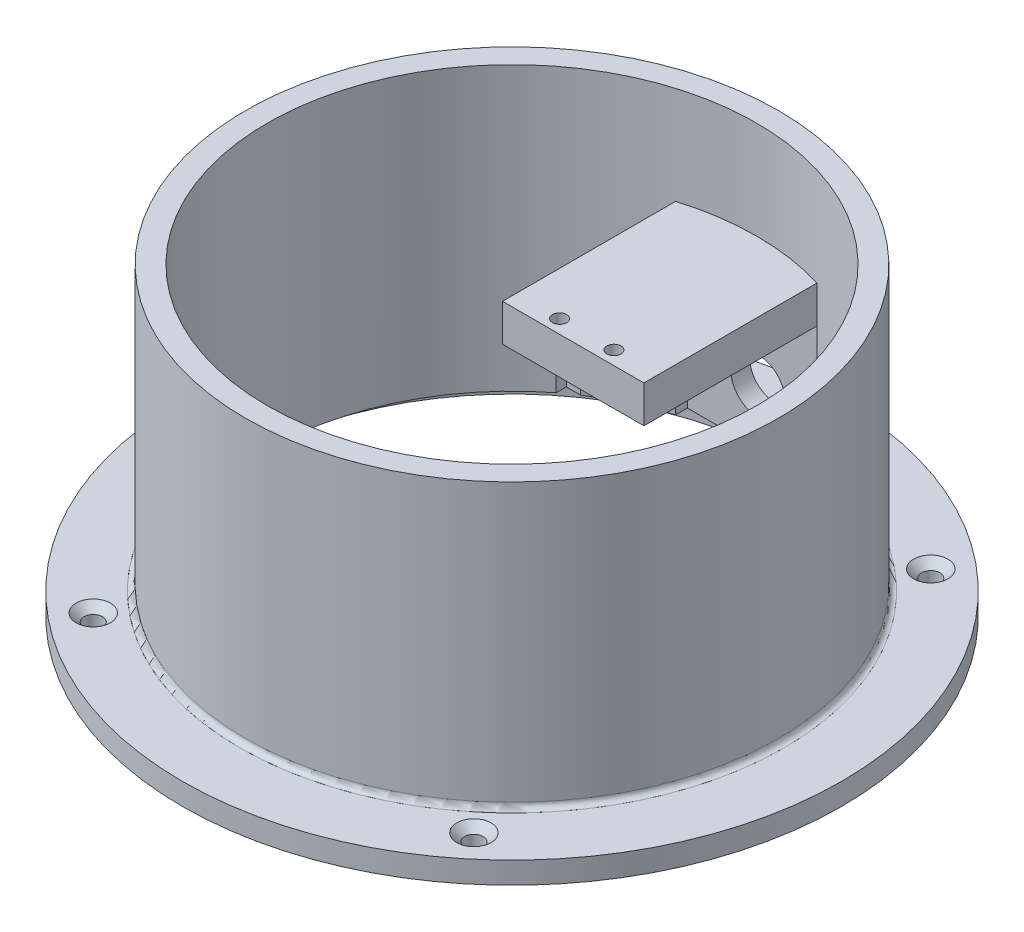
SolidWorks part; units mm, degrees
ref_plane "Front Plane" through (0, 0, 0) normal (0, 0, 1) x (1, 0, 0)
ref_plane "Top Plane" through (0, 0, 0) normal (0, 1, 0) x (1, 0, 0)
ref_plane "Right Plane" through (0, 0, 0) normal (1, 0, 0) x (0, 0, -1)
sketch "Sketch1" plane through (0, 0, 0) normal (0, 1, 0) x (1, 0, 0)
  circle A0 centre (0, 0) radius 60.625
  circle A1 centre (0, 0) radius 45
  dimension "D1" = 121.25
  dimension "D2" = 90
extrude "Boss-Extrude1" add sketch "Sketch1" along normal blind 4
sketch "Sketch2" plane through (0, 4, 0) normal (0, 1, 0) x (1, 0, 0)
  circle A0 centre (0, 0) radius 45 construction
  circle A1 centre (0, 0) radius 45
  circle A2 centre (0, 0) radius 49
  dimension "D1" = 4
extrude "Boss-Extrude2" add sketch "Sketch2" along normal blind 52
sketch "Sketch3" plane through (0, 0, 0) normal (1, 0, 0) x (0, 0, -1)
  line L0 (-46.75, 30) -> (-31.75, 30)
  line L1 (-31.75, 30) -> (-31.75, 38)
  line L2 (-31.75, 38) -> (-46.75, 38)
  line L3 (-46.75, 38) -> (-46.75, 30)
  line L4 (-45, 56) -> (-45, 0)
  line L5 (-31.75, 38) -> (-45, 24.75)
  line L6 (-45, 0) -> (45, 0) construction
  line L7 (11.25, 38) -> (19.25, 38)
  line L8 (11.25, 38) -> (11.25, 0)
  line L9 (11.25, 0) -> (19.25, 0)
  line L10 (19.25, 38) -> (19.25, 0)
  line L11 (11.25, 38) -> (19.25, 0) construction
  line L12 (11.25, 0) -> (19.25, 38) construction
  line L13 (49, 56) -> (-49, 56) construction
  line L14 (45, 56) -> (-45, 56) construction
  point P8 (15.25, 19)
  dimension "D1" = 8
  dimension "D2" = 18
  dimension "D3" = 11.25
  dimension "D4" = 43
  dimension "D5" = 15
  dimension "D6" = 45
  dimension "D7" = 8
  dimension "D8" = 18
extrude "Boss-Extrude3" add sketch "Sketch3" along normal mid plane 26 contours L10 L7 L8 L9 | L5 L2 L4 L0 | L5 L0 L4 | L1 L5 L0
sketch "Sketch6" plane through (0, 0, -11.25) normal (0, 0, 1) x (1, 0, 0)
  line L0 (13, 38) -> (-13, 38) construction
  line L5 (-5, 29) -> (5, 29)
  line L6 (-5, 29) -> (-5, 5)
  line L7 (-5, 5) -> (5, 5)
  line L8 (5, 29) -> (5, 5)
  line L9 (-5, 29) -> (5, 5) construction
  line L10 (-5, 5) -> (5, 29) construction
  point P0 (0, 17)
  point P8 (0, 5)
  dimension "D1" = 10
  dimension "D2" = 9
  dimension "D3" = 5
extrude "Cut-Extrude1" cut sketch "Sketch6" against normal blind 26
sketch "Sketch7" plane through (0, 0, -11.25) normal (0, 0, 1) x (1, 0, 0)
  line L0 (0, 56) -> (0, 0) construction
  circle A0 centre (0, 14) radius 5
  dimension "D1" = 10
  dimension "D2" = 14
extrude "Cut-Extrude2" cut sketch "Sketch7" against normal blind 58
sketch "Sketch8" plane through (0, 38, 0) normal (0, 1, 0) x (1, 0, 0)
  line L0 (-5, 13.75) -> (5, 13.75) construction
  line L1 (-5, -34.25) -> (5, -34.25) construction
  line L2 (13, -31.75) -> (-13, -31.75) construction
  circle A0 centre (-5, 13.75) radius 1.3
  circle A1 centre (5, 13.75) radius 1.3
  circle A2 centre (-5, -34.25) radius 1.3
  circle A3 centre (5, -34.25) radius 1.3
  dimension "D1" = 2.6
  dimension "D2" = 5
  dimension "D3" = 10
  dimension "D4" = 10
  dimension "D5" = 2.5
  dimension "D6" = 48
extrude "Cut-Extrude3" cut sketch "Sketch8" against normal blind 7.2
sketch "Sketch10" plane through (0, 4, 0) normal (0, 1, 0) x (1, 0, 0)
  line L1 (-35, -42) -> (35, -42) construction
  line L2 (-35, -42) -> (-35, 42) construction
  line L3 (-35, 42) -> (35, 42) construction
  line L4 (35, -42) -> (35, 42) construction
  line L5 (-35, -42) -> (35, 42) construction
  line L6 (-35, 42) -> (35, -42) construction
  point P0 (0, 0)
  dimension "D1" = 84
  dimension "D2" = 70
hole_wizard "CSK for M3 Countersunk Flat Head Screw1" positions "Sketch11" profile "Sketch12" countersink size "M3" standard "DIN"
sketch "Sketch11" plane through (0, 4, 0) normal (0, 1, 0) x (1, 0, 0)
  point P0 (-35, 42)
  point P3 (35, 42)
  point P6 (35, -42)
  point P9 (-35, -42)
sketch "Sketch12" plane through (-35, 4, -42) normal (1, 0, 0) x (0, 0, 1)
  line L0 (0, 0) -> (0, 5.0215)
  line L1 (0, 5.0215) -> (1.7, 4)
  line L2 (1.7, 4) -> (1.7, 1.45)
  line L3 (1.7, 1.45) -> (3.15, 0)
  line L5 (3.15, 0) -> (0, 0)
  line L6 (-1.7, 1.45) -> (-3.15, 0) construction
  line L10 (0, 5.0215) -> (-1.7, 4) construction
  line L11 (0, -6.35) -> (0, 107.95) construction
  dimension "Hole Dia." = 3.4
  dimension "Hole Depth" = 4
  dimension "Near C'Sink Dia." = 6.3
  dimension "Near C'Sink Angle" = 90
  dimension "Drill Angle" = 118
fillet "Fillet1" radius 1 1 edges at (0, 4, 49)
sketch "Sketch13" plane through (0, 0, -19.25) normal (0, 0, -1) x (-1, 0, 0)
  line L4 (13, 0) -> (13, 38)
  line L5 (13, 38) -> (-13, 38)
  line L6 (-13, 38) -> (-13, 0)
  line L7 (-13, 0) -> (13, 0)
  line L8 (13, 0) -> (13, 38)
  line L9 (13, 38) -> (-13, 38)
  line L10 (-13, 38) -> (-13, 0)
  line L11 (-13, 0) -> (13, 0)
  dimension "D1" = 0
extrude "Boss-Extrude4" add sketch "Sketch13" along normal up to surface (23.8313 mm away)
sketch "Sketch14" plane through (0, 0, -11.25) normal (0, 0, 1) x (1, 0, 0)
  line L0 (-13, 26.1719) -> (13, 26.1719)
  line L1 (-13, 38) -> (-13, 0) construction
  line L2 (13, 38) -> (13, 0) construction
  line L3 (13, 26.1719) -> (13, 0)
  line L4 (13, 0) -> (-13, 0) construction
  line L5 (13, 0) -> (-13, 0)
  line L6 (-13, 0) -> (-13, 26.1719)
extrude "Cut-Extrude4" cut sketch "Sketch14" against normal blind 34
sketch "Sketch15" plane through (0, 0, 0) normal (0, -1, 0) x (1, 0, 0)
  line L0 (-29.5, 39.5) -> (29.5, 39.5)
  line L1 (-27.5, -37.5) -> (27.5, -37.5)
  line L2 (-27.5, -37.5) -> (-27.5, 37.5)
  line L3 (-27.5, 37.5) -> (27.5, 37.5)
  line L4 (27.5, -37.5) -> (27.5, 37.5)
  line L5 (-27.5, -37.5) -> (27.5, 37.5) construction
  line L6 (-27.5, 37.5) -> (27.5, -37.5) construction
  line L7 (29.5, -39.5) -> (29.5, 39.5)
  line L8 (-29.5, -39.5) -> (29.5, -39.5)
  line L9 (-29.5, -39.5) -> (-29.5, 39.5)
  circle A0 centre (0, 0) radius 50
  point P0 (0, 0)
  arc M5 (-13, -43.0813) -> (13, -43.0813) centre (0, 0) cw
  dimension "D3" = 100
  dimension "D1" = 75
  dimension "D2" = 55
  dimension "D4" = 2
extrude "Cut-Extrude6" cut sketch "Sketch15" against normal blind 7 contours L1 L4 M5 | L4 L3 M5 | L3 L2 M5 | L2 L1 M5
sketch "Sketch17" plane through (0, 26.1719, 0) normal (0, -1, 0) x (1, 0, 0)
  line L10 (5, -19.25) -> (-5, -19.25)
  line L11 (-5, -19.25) -> (-5, -11.25)
  line L12 (-5, -11.25) -> (-13, -11.25)
  line L13 (-13, -11.25) -> (-13, -43.0813)
  line L14 (-13, -43.0813) -> (-13, -45.25)
  line L15 (-13, -45.25) -> (13, -45.25)
  line L16 (13, -45.25) -> (13, -43.0813)
  line L17 (13, -43.0813) -> (13, -11.25)
  line L18 (13, -11.25) -> (5, -11.25)
  line L19 (5, -11.25) -> (5, -19.25)
  line L20 (5, -19.25) -> (-5, -19.25)
  line L21 (-5, -19.25) -> (-5, -11.25)
  line L22 (-5, -11.25) -> (-13, -11.25)
  line L23 (-13, -11.25) -> (-13, -43.0813)
  line L24 (-13, -43.0813) -> (-13, -45.25)
  line L25 (-13, -45.25) -> (13, -45.25)
  line L26 (13, -45.25) -> (13, -43.0813)
  line L27 (13, -43.0813) -> (13, -11.25)
  line L28 (13, -11.25) -> (5, -11.25)
  line L29 (5, -11.25) -> (5, -19.25)
  dimension "D1" = 0
extrude "Cut-Extrude10" cut sketch "Sketch17" against normal blind 5
sketch "Sketch18" plane through (0, 29, 0) normal (0, -1, 0) x (1, 0, 0)
  line L4 (-5, -19.25) -> (5, -19.25)
  line L5 (5, -19.25) -> (5, -11.25)
  line L6 (5, -11.25) -> (-5, -11.25)
  line L7 (-5, -11.25) -> (-5, -19.25)
  line L8 (-5, -19.25) -> (5, -19.25)
  line L9 (5, -19.25) -> (5, -11.25)
  line L10 (5, -11.25) -> (-5, -11.25)
  line L11 (-5, -11.25) -> (-5, -19.25)
  dimension "D1" = 0
extrude "Cut-Extrude11" cut sketch "Sketch18" against normal blind 2
sketch "Sketch19" plane through (0, 31, 0) normal (0, -1, 0) x (1, 0, 0)
  line L6 (5, -12.45) -> (5, -11.25)
  line L7 (5, -11.25) -> (-5, -11.25)
  line L8 (-5, -11.25) -> (-5, -12.45)
  line L9 (-5, -15.05) -> (-5, -19.25)
  line L10 (-5, -19.25) -> (5, -19.25)
  line L11 (5, -19.25) -> (5, -15.05)
  line L12 (5, -12.45) -> (5, -11.25)
  line L13 (5, -11.25) -> (-5, -11.25)
  line L14 (-5, -11.25) -> (-5, -12.45)
  line L15 (-5, -15.05) -> (-5, -19.25)
  line L16 (-5, -19.25) -> (5, -19.25)
  line L17 (5, -19.25) -> (5, -15.05)
  arc A2 (5, -12.45) -> (5, -15.05) centre (5, -13.75) ccw
  arc A3 (-5, -15.05) -> (-5, -12.45) centre (-5, -13.75) ccw
  arc A4 (5, -12.45) -> (5, -15.05) centre (5, -13.75) ccw
  arc A5 (-5, -15.05) -> (-5, -12.45) centre (-5, -13.75) ccw
  dimension "D1" = 0
extrude "Cut-Extrude12" cut sketch "Sketch19" against normal blind 0.15
sketch "Sketch20" plane through (0, 0, 0) normal (0, -1, 0) x (1, 0, 0)
  circle A0 centre (0, 0) radius 50
  dimension "D1" = 100
extrude "Cut-Extrude13" cut sketch "Sketch20" against normal blind 4
sketch "Sketch22" plane through (0, 4, 0) normal (0, -1, 0) x (1, 0, 0)
  line L0 (0, 50) -> (0, -50) construction
  line L1 (-50, 0) -> (-45, 0) construction
  circle A0 centre (0, 0) radius 50 construction
  circle A1 centre (0, 0) radius 50 construction
  arc A2 (-27.5, 35.6195) -> (-27.5, -35.6195) centre (0, 0) ccw construction
  circle A3 centre (-47.5, 0) radius 1
  circle A4 centre (47.5, 0) radius 1
  point P14 (0, 0)
  point P15 (-47.5, 0)
  dimension "D1" = 2
extrude "Cut-Extrude16" cut sketch "Sketch22" against normal blind 4
